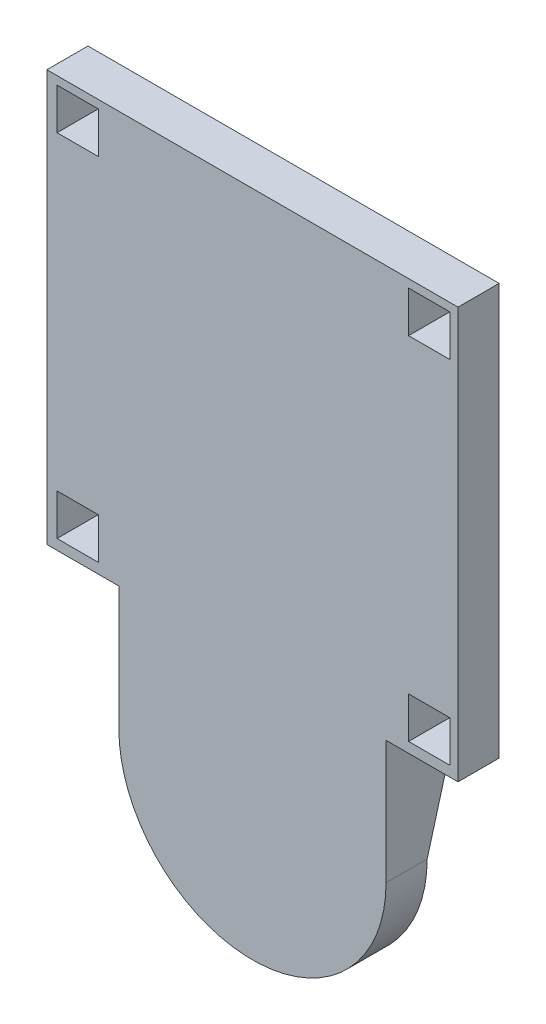
SolidWorks part; units mm, degrees
ref_plane "前视基准面" through (0, 0, 0) normal (0, 0, 1) x (1, 0, 0)
ref_plane "上视基准面" through (0, 0, 0) normal (0, 1, 0) x (1, 0, 0)
ref_plane "右视基准面" through (0, 0, 0) normal (1, 0, 0) x (0, 0, -1)
other "Configuration Table"
sketch "草图1" plane through (0, 0, 0) normal (0, 0, 1) x (1, 0, 0)
  line L1 (-100, -100) -> (100, -100)
  line L2 (-100, -100) -> (-100, 100)
  line L3 (-100, 100) -> (100, 100)
  line L4 (100, -100) -> (100, 100)
  line L5 (-100, -100) -> (100, 100) construction
  line L6 (-100, 100) -> (100, -100) construction
  point P0 (0, 0)
  dimension "D1" = 200
  dimension "D2" = 200
extrude "凸台-拉伸1" add sketch "草图1" along normal mid plane 20
sketch "草图2" plane through (0, 0, -10) normal (0, 0, -1) x (-1, 0, 0)
  line L0 (-100, 100) -> (100, 100) construction
  line L1 (-75.95, 75.95) -> (-96, 75.95)
  line L2 (-75.95, 75.95) -> (-75.95, 96)
  line L3 (-75.95, 96) -> (-96, 96)
  line L4 (-96, 75.95) -> (-96, 96)
  line L5 (-75.95, 75.95) -> (-96, 96) construction
  line L6 (-75.95, 96) -> (-96, 75.95) construction
  line L7 (75, 75.95) -> (95.05, 75.95)
  line L8 (75, 75.95) -> (75, 96)
  line L9 (75, 96) -> (95.05, 96)
  line L10 (95.05, 75.95) -> (95.05, 96)
  line L11 (75, 75.95) -> (95.05, 96) construction
  line L12 (75, 96) -> (95.05, 75.95) construction
  line L13 (95.05, -95) -> (75, -95)
  line L14 (95.05, -95) -> (95.05, -74.95)
  line L15 (95.05, -74.95) -> (75, -74.95)
  line L16 (75, -95) -> (75, -74.95)
  line L17 (95.05, -95) -> (75, -74.95) construction
  line L18 (95.05, -74.95) -> (75, -95) construction
  line L19 (-96, -95) -> (-75.95, -95)
  line L20 (-96, -95) -> (-96, -74.95)
  line L21 (-96, -74.95) -> (-75.95, -74.95)
  line L22 (-75.95, -95) -> (-75.95, -74.95)
  line L23 (-96, -95) -> (-75.95, -74.95) construction
  line L24 (-96, -74.95) -> (-75.95, -95) construction
  line L25 (-100, -100) -> (-100, 100) construction
  line L26 (100, 100) -> (100, -100) construction
  line L27 (100, -100) -> (-100, -100) construction
  point P0 (-85.975, 85.975)
  point P5 (85.025, 85.975)
  point P10 (85.025, -84.975)
  point P15 (-85.975, -84.975)
  dimension "D1" = 4
  dimension "D2" = 4
  dimension "D3" = 4
  dimension "D4" = 4.95
  dimension "D5" = 4.95
  dimension "D6" = 5
  dimension "D7" = 5
  dimension "D8" = 4
  dimension "D9" = 20.05
  dimension "D10" = 20.05
  dimension "D11" = 20.05
  dimension "D12" = 20.05
  dimension "D13" = 20.05
  dimension "D14" = 20.05
  dimension "D15" = 20.05
  dimension "D16" = 20.05
extrude "切除-拉伸2" cut sketch "草图2" against normal blind 40
sketch "草图3" plane through (0, 0, -10) normal (0, 0, -1) x (-1, 0, 0)
  circle A0 centre (-3.6147, -72.424) radius 17.0214
sketch "草图5" plane through (0, -100, 0) normal (0, -1, 0) x (1, 0, 0)
  line L0 (-65, -10) -> (65, -10)
  line L1 (-100, -10) -> (100, -10) construction
  line L2 (65, -10) -> (65, 10)
  line L3 (-100, 10) -> (100, 10) construction
  line L4 (65, 10) -> (-65, 10)
  line L5 (-65, 10) -> (-65, -10)
  point P0 (-59.111, -17.7439)
  point P5 (0, -10)
  point P10 (0, -10)
  dimension "D1" = 130
extrude "凸台-拉伸2" add sketch "草图5" along normal blind 60
sketch "草图6" plane through (0, 0, -10) normal (0, 0, -1) x (-1, 0, 0)
  line L0 (65, -160) -> (-65, -160) construction
  line L1 (-65, -160) -> (65, -160)
  arc A0 (-65, -160) -> (65, -160) centre (0, -160) ccw
extrude "凸台-拉伸3" add sketch "草图6" against normal blind 20
sketch "草图7" plane through (0, 0, -10) normal (0, 0, -1) x (-1, 0, 0)
  line L1 (-55, -100) -> (-55, -80.5)
  line L2 (-55, -80.5) -> (55, -80.5)
  line L3 (55, -80.5) -> (55, -100)
  line L6 (55, -100) -> (55, -160)
  line L7 (-55, -160) -> (-55, -100)
  line L8 (55, -100) -> (55, -160)
  line L9 (-55, -160) -> (-55, -100)
  arc A3 (-55, -160) -> (55, -160) centre (0, -160) ccw
  arc A4 (-55, -160) -> (55, -160) centre (0, -160) ccw
  dimension "D2" = 19.5
  dimension "D1" = 10
extrude "切除-拉伸4" cut sketch "草图7" against normal blind 16
sketch "草图10" plane through (0, 0, 6) normal (0, 0, -1) x (-1, 0, 0)
  line L0 (-55, -80.5) -> (-55, -90.5)
  line L1 (-55, -80.5) -> (-55, -160) construction
  line L2 (-55, -90.5) -> (55, -90.5)
  line L3 (55, -160) -> (55, -80.5) construction
  line L4 (55, -90.5) -> (55, -80.5)
  line L5 (55, -80.5) -> (-55, -80.5)
  dimension "D1" = 10
extrude "凸台-拉伸5" add sketch "草图10" along normal blind 38
sketch "草图11" plane through (55, 0, 0) normal (1, 0, 0) x (0, 0, -1)
  line L0 (32, -80.5) -> (10, -80.5)
  line L1 (10, -80.5) -> (10, -160)
  line L2 (10, -160) -> (32, -80.5)
extrude "凸台-拉伸6" add sketch "草图11" along normal blind 10
mirror "镜向1" about plane through (0, 0, 0) normal (1, 0, 0) of "凸台-拉伸6"
sketch "草图12" plane through (-55, 0, 0) normal (1, 0, 0) x (0, 0, -1)
  line L1 (-6, -160) -> (-6, -90.5) construction
  line L2 (-6, -125.5) -> (-6, -90.5)
  line L4 (-6, -90.5) -> (23, -90.5)
  line L5 (29.2327, -90.5) -> (-6, -90.5) construction
  line L6 (23, -90.5) -> (-6, -125.5)
  dimension "D1" = 35
  dimension "D2" = 29
extrude "凸台-拉伸7" add sketch "草图12" along normal blind 120
